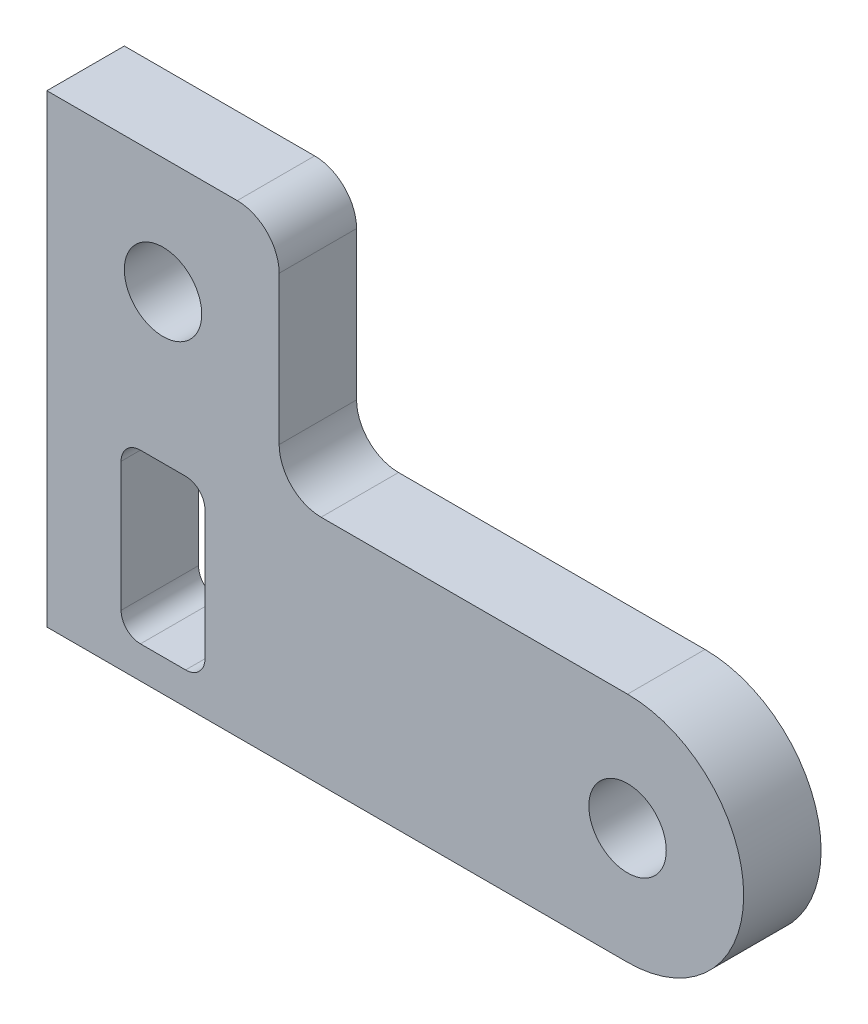
SolidWorks part; units mm, degrees
ref_plane "Alzado" through (0, 0, 0) normal (0, 0, 1) x (1, 0, 0)
ref_plane "Planta" through (0, 0, 0) normal (0, 1, 0) x (1, 0, 0)
ref_plane "Vista lateral" through (0, 0, 0) normal (1, 0, 0) x (0, 0, -1)
sketch "Model" plane through (0, 0, 0) normal (0, 0, 1) x (1, 0, 0)
  line L0 (182.2229, 265.8965) -> (183.9729, 265.8965)
  line L1 (184.7229, 266.6465) -> (184.7229, 271.6465)
  line L2 (183.9729, 272.3965) -> (182.2229, 272.3965)
  line L3 (181.4729, 271.6465) -> (181.4729, 266.6465)
  line L4 (185.9729, 282.6465) -> (178.5979, 282.6465)
  line L5 (178.5979, 282.6465) -> (178.5979, 264.6465)
  line L6 (187.5979, 281.0215) -> (187.5979, 275.2715)
  line L7 (189.2229, 273.6465) -> (201.0979, 273.6465)
  line L8 (201.0979, 264.6465) -> (178.5979, 264.6465)
  circle A0 centre (201.0979, 269.1465) radius 1.5
  arc A1 (181.4729, 266.6465) -> (182.2229, 265.8965) centre (182.2229, 266.6465) ccw
  arc A2 (183.9729, 265.8965) -> (184.7229, 266.6465) centre (183.9729, 266.6465) ccw
  arc A3 (184.7229, 271.6465) -> (183.9729, 272.3965) centre (183.9729, 271.6465) ccw
  arc A4 (182.2229, 272.3965) -> (181.4729, 271.6465) centre (182.2229, 271.6465) ccw
  arc A5 (201.0979, 264.6465) -> (201.0979, 273.6465) centre (201.0979, 269.1465) ccw
  arc A6 (187.5979, 275.2715) -> (189.2229, 273.6465) centre (189.2229, 275.2715) ccw
  arc A7 (187.5979, 281.0215) -> (185.9729, 282.6465) centre (185.9729, 281.0215) ccw
  circle A8 centre (183.0979, 278.146) radius 1.5
extrude "Saliente-Extruir1" add sketch "Model" along normal blind 3
